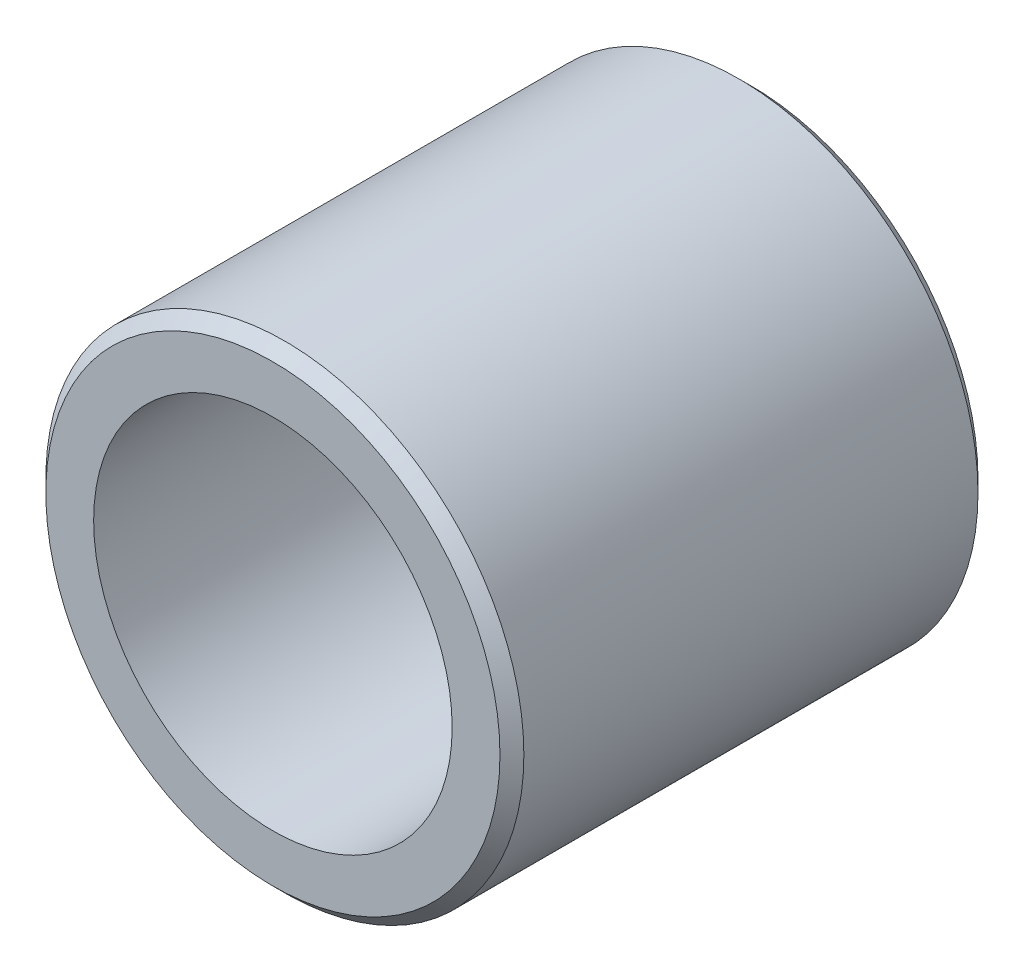
SolidWorks part; units mm, degrees
ref_plane "Front Plane" through (0, 0, 0) normal (0, 0, 1) x (1, 0, 0)
ref_plane "Top Plane" through (0, 0, 0) normal (0, 1, 0) x (1, 0, 0)
ref_plane "Right Plane" through (0, 0, 0) normal (1, 0, 0) x (0, 0, -1)
sketch "Sketch1" plane through (0, 0, 0) normal (0, 0, 1) x (1, 0, 0)
  circle A0 centre (0, 0) radius 19.05
  circle A1 centre (0, 0) radius 25.4
  dimension "D1" = 38.1
  dimension "D2" = 50.8
extrude "Boss-Extrude1" add sketch "Sketch1" along normal blind 50.8
chamfer "Chamfer1" distance 1.27 angle 45 1 edges at (25.4, 0, 0)
chamfer "Chamfer2" distance 1.27 angle 45 1 edges at (25.4, 0, 50.8)
sketch "Sketch2" plane through (0, 0, 0) normal (0, 1, 0) x (1, 0, 0)
  line L0 (0, -51.0808) -> (0, 0)
